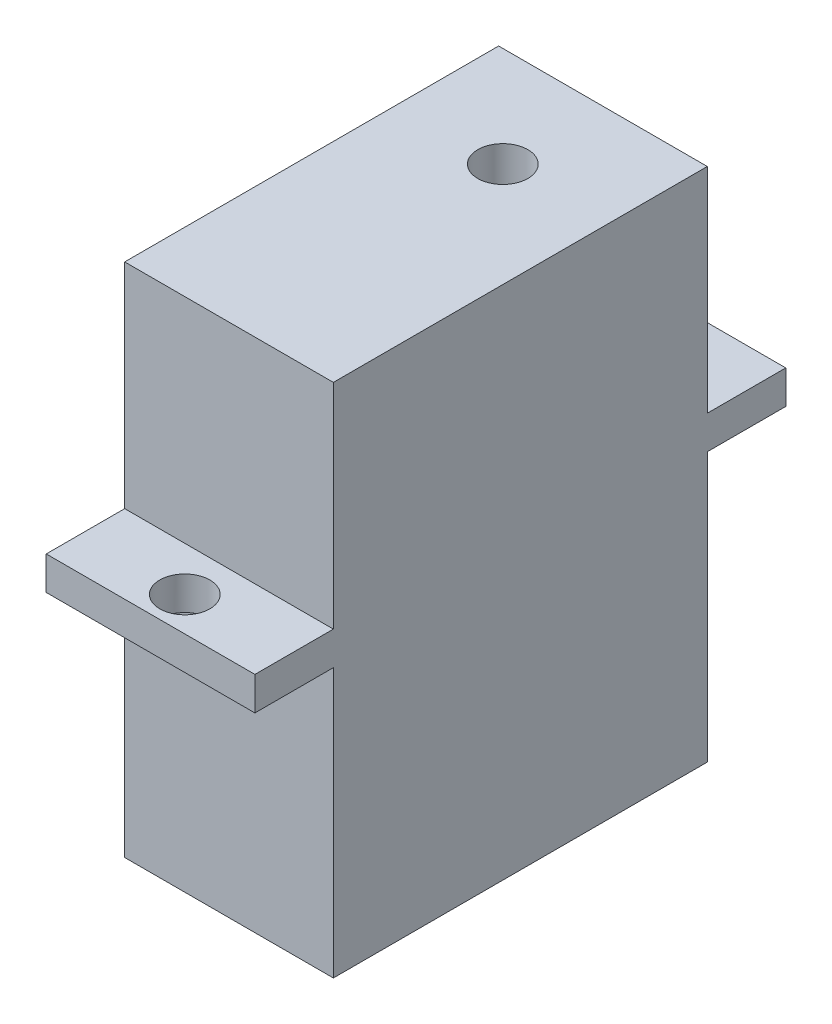
SolidWorks part; units mm, degrees
ref_plane "前视基准面" through (0, 0, 0) normal (0, 0, 1) x (1, 0, 0)
ref_plane "上视基准面" through (0, 0, 0) normal (0, 1, 0) x (1, 0, 0)
ref_plane "右视基准面" through (0, 0, 0) normal (1, 0, 0) x (0, 0, -1)
sketch "草图1" plane through (0, 0, 0) normal (0, 1, 0) x (1, 0, 0)
  line L1 (-6.25, 11.2) -> (6.25, 11.2)
  line L2 (-6.25, 11.2) -> (-6.25, -11.2)
  line L3 (-6.25, -11.2) -> (6.25, -11.2)
  line L4 (6.25, 11.2) -> (6.25, -11.2)
  line L5 (-6.25, 11.2) -> (6.25, -11.2) construction
  line L6 (-6.25, -11.2) -> (6.25, 11.2) construction
  point P0 (0, 0)
  dimension "D1" = 12.5
  dimension "D2" = 22.4
extrude "凸台-拉伸1" add sketch "草图1" along normal blind 30.9
sketch "草图4" plane through (6.25, 0, 0) normal (1, 0, 0) x (0, 0, -1)
  line L0 (0, 0) -> (0, 16.1) construction
  line L2 (-15.9, 16.1) -> (15.9, 16.1)
  line L3 (-15.9, 16.1) -> (-15.9, 18.1)
  line L4 (-15.9, 18.1) -> (15.9, 18.1)
  line L5 (15.9, 16.1) -> (15.9, 18.1)
  dimension "D1" = 16.1
  dimension "D2" = 2
  dimension "2" = 31.8
extrude "凸台-拉伸2" add sketch "草图4" against normal blind 12.5
sketch "草图6" plane through (0, 18.1, 0) normal (0, 1, 0) x (1, 0, 0)
  line L0 (0, -13.85) -> (0, 13.85) construction
  circle A2 centre (0, 13.85) radius 1.5
  circle A3 centre (0, -13.85) radius 1.5
  point P3 (0, 0)
  dimension "D1" = 27.7
  dimension "D2" = 3
  dimension "D3" = 3
extrude "切除-拉伸2" cut sketch "草图6" against normal through all
sketch "草图7" plane through (0, 30.9, 0) normal (0, 1, 0) x (1, 0, 0)
  line L0 (0, 11.2) -> (0, 5.2) construction
  line L1 (6.25, 11.2) -> (-6.25, 11.2) construction
  line L2 (-6.25, 15.9) -> (6.25, 15.9) construction
  circle A0 centre (0, 5.2) radius 1.5
  dimension "D2" = 3
  dimension "D1" = 6
  dimension "D3" = 10.7
extrude "切除-拉伸3" cut sketch "草图7" against normal blind 3
